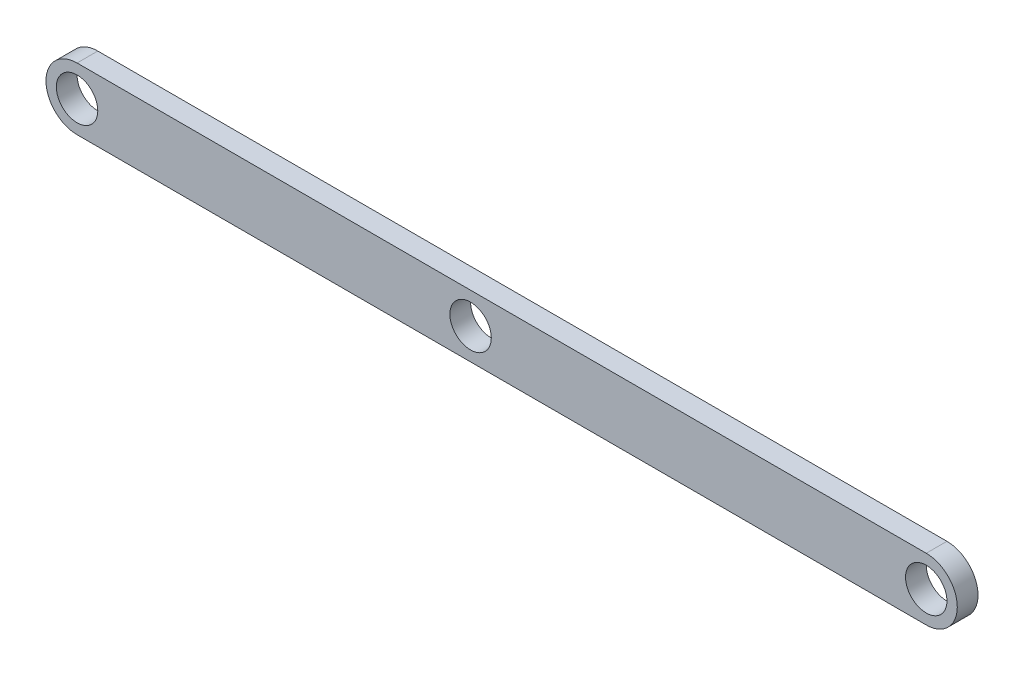
SolidWorks part; units mm, degrees
ref_plane "Спереди" through (0, 0, 0) normal (0, 0, 1) x (1, 0, 0)
ref_plane "Сверху" through (0, 0, 0) normal (0, 1, 0) x (1, 0, 0)
ref_plane "Справа" through (0, 0, 0) normal (1, 0, 0) x (0, 0, -1)
other "Configuration Table"
sketch "Эскиз2" plane through (0, 0, 0) normal (0, 0, 1) x (1, 0, 0)
  line L0 (0, 0) -> (410, 0) construction
  line L1 (0, 15) -> (410, 15)
  line L2 (0, -15) -> (410, -15)
  line L3 (0, -1000) -> (0, 49000) construction
  line L4 (190, -1000) -> (190, 49000) construction
  arc A0 (0, 15) -> (0, -15) centre (0, 0) ccw
  arc A1 (410, -15) -> (410, 15) centre (410, 0) ccw
  circle A2 centre (0, 0) radius 10
  circle A3 centre (410, 0) radius 10
  circle A4 centre (190, 0) radius 10
  point P3 (205, 0)
  point P15 (190, 0)
  dimension "D3" = 190
  dimension "D1" = 410
  dimension "D2" = 30
extrude "Бобышка-Вытянуть1" add sketch "Эскиз2" along normal blind 10
